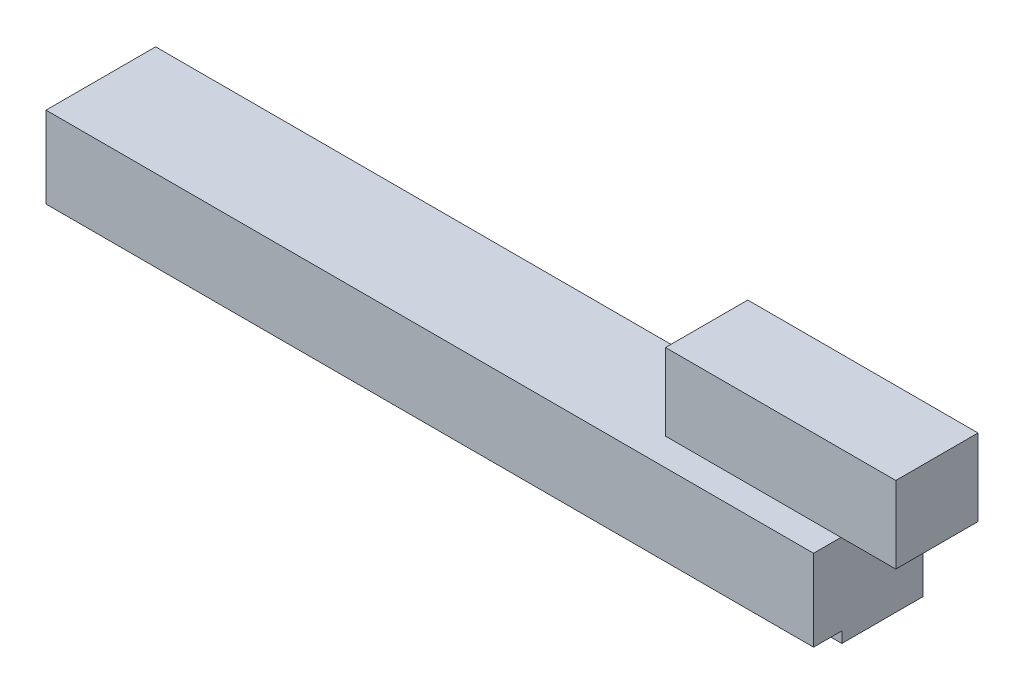
SolidWorks part; units mm, degrees
ref_plane "Front Plane" through (0, 0, 0) normal (0, 0, 1) x (1, 0, 0)
ref_plane "Top Plane" through (0, 0, 0) normal (0, 1, 0) x (1, 0, 0)
ref_plane "Right Plane" through (0, 0, 0) normal (1, 0, 0) x (0, 0, -1)
sketch "Sketch1" plane through (0, 0, 0) normal (1, 0, 0) x (0, 0, -1)
  line L0 (-10, -6.42) -> (-4.84, -6.42)
  line L1 (-10, -8.42) -> (10, -8.42)
  line L2 (-10, -8.42) -> (-10, 8.42)
  line L3 (-10, 8.42) -> (10, 8.42)
  line L4 (10, -8.42) -> (10, 8.42)
  line L5 (-10, -8.42) -> (10, 8.42) construction
  line L6 (-10, 8.42) -> (10, -8.42) construction
  line L7 (-4.84, -6.42) -> (-4.84, -8.42)
  point P0 (0, 0)
  dimension "D1" = 16.84
  dimension "D2" = 20
  dimension "D3" = 2
  dimension "D4" = 5.16
extrude "Boss-Extrude1" add sketch "Sketch1" along normal blind 140 contours L0 L7 L1 L4 L3 L2
sketch "Sketch2" plane through (0, 8.42, 0) normal (0, 1, 0) x (1, 0, 0)
  line L0 (108, 10) -> (150, 10)
  line L5 (108, 10) -> (108, -5)
  line L6 (108, -5) -> (150, -5)
  line L7 (150, 10) -> (150, -5)
  line L8 (0, -10) -> (0, 10) construction
  dimension "D1" = 108
  dimension "D3" = 15
  dimension "D4" = 42
extrude "Boss-Extrude2" add sketch "Sketch2" along normal blind 14
